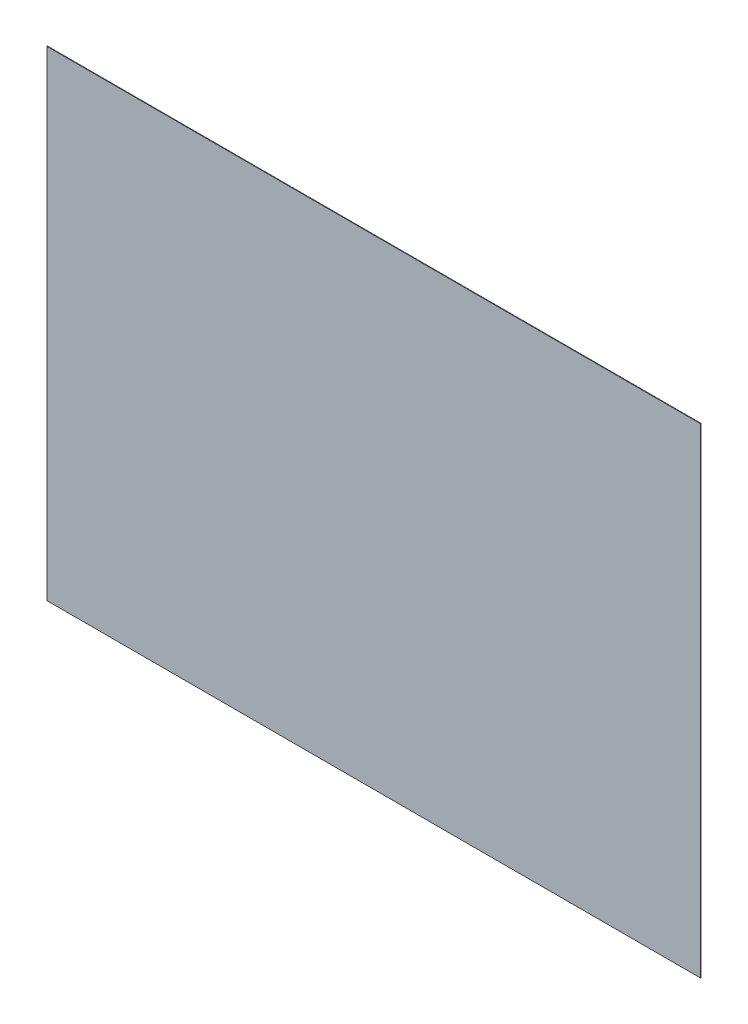
SolidWorks part; units mm, degrees
ref_plane "Plan de face" through (0, 0, 0) normal (0, 0, 1) x (1, 0, 0)
ref_plane "Plan de dessus" through (0, 0, 0) normal (0, 1, 0) x (1, 0, 0)
ref_plane "Plan de droite" through (0, 0, 0) normal (1, 0, 0) x (0, 0, -1)
sketch "Esquisse1" plane through (0, 0, 0) normal (0, 0, 1) x (1, 0, 0)
  line L1 (-28.8, -21.15) -> (28.8, -21.15)
  line L2 (-28.8, -21.15) -> (-28.8, 21.15)
  line L3 (-28.8, 21.15) -> (28.8, 21.15)
  line L4 (28.8, -21.15) -> (28.8, 21.15)
  line L5 (-28.8, -21.15) -> (28.8, 21.15) construction
  line L6 (-28.8, 21.15) -> (28.8, -21.15) construction
  point P0 (0, 0)
  dimension "D1" = 57.6
  dimension "D2" = 42.3
extrude "Boss.-Extru.1" add sketch "Esquisse1" along normal blind 0.05
